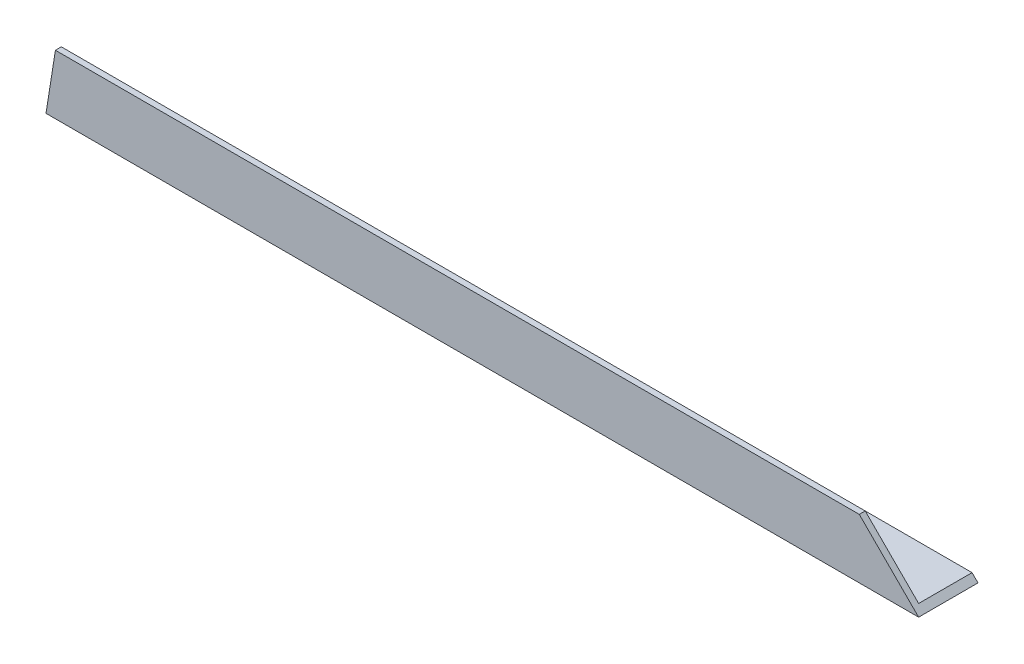
SolidWorks part; units mm, degrees
ref_plane "Front Plane" through (0, 0, 0) normal (0, 0, 1) x (1, 0, 0)
ref_plane "Top Plane" through (0, 0, 0) normal (0, 1, 0) x (1, 0, 0)
ref_plane "Right Plane" through (0, 0, 0) normal (1, 0, 0) x (0, 0, -1)
sketch "Sketch1" plane through (0, 0, 0) normal (1, 0, 0) x (0, 0, -1)
  line L0 (0, 20) -> (0, 0)
  line L1 (0, 0) -> (20, 0)
  line L2 (20, 0) -> (20, 2)
  line L3 (20, 2) -> (2, 2)
  line L4 (2, 2) -> (2, 20)
  line L5 (0, 20) -> (2, 20)
  dimension "D1" = 20
  dimension "D2" = 20
  dimension "D3" = 2
  dimension "D4" = 2
extrude "Boss-Extrude1" add sketch "Sketch1" along normal blind 294
sketch "Sketch2" plane through (0, 0, 0) normal (0, 0, -1) x (-1, 0, 0)
  line L0 (0, 0) -> (-3.1677, 20)
  line L1 (-294, 20) -> (0, 20) construction
  line L2 (-3.1677, 20) -> (0, 20)
  line L3 (0, 20) -> (0, 0)
  line L4 (-294, 0) -> (-274, 20)
  line L5 (-274, 20) -> (-294, 20)
  line L6 (-294, 20) -> (-294, 0)
  dimension "D1" = 45
  dimension "D2" = 9
extrude "Cut-Extrude1" cut sketch "Sketch2" along normal through all
